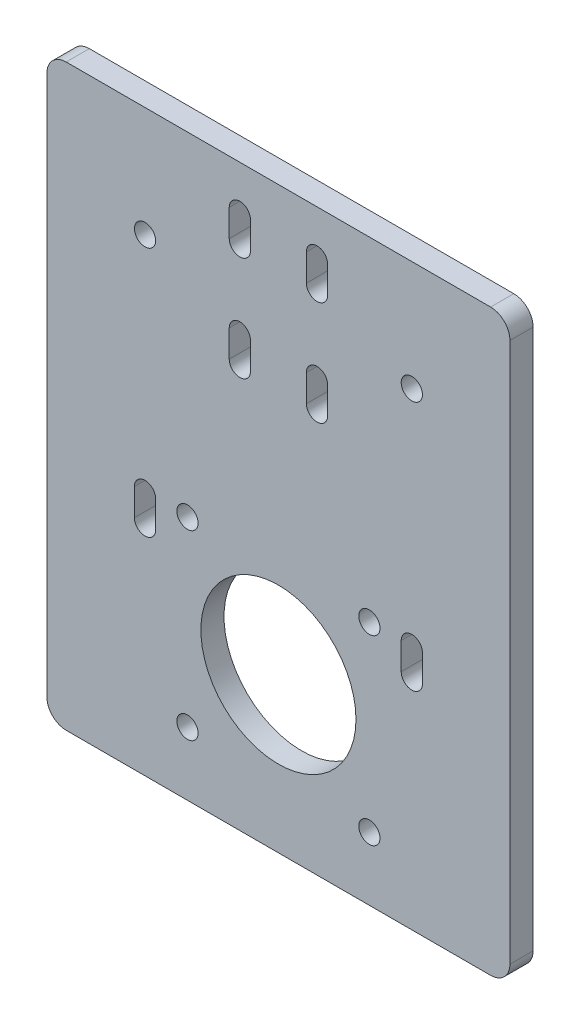
SolidWorks part; units mm, degrees
material "PET"
ref_plane "Front Plane" through (0, 0, 0) normal (0, 0, 1) x (1, 0, 0)
ref_plane "Top Plane" through (0, 0, 0) normal (0, 1, 0) x (1, 0, 0)
ref_plane "Right Plane" through (0, 0, 0) normal (1, 0, 0) x (0, 0, -1)
sketch "Sketch3" plane through (0, 0, 0) normal (0, 0, 1) x (1, 0, 0)
  line L1 (-55, -75) -> (55, -75)
  line L2 (-60, -70) -> (-60, 70)
  line L3 (-55, 75) -> (55, 75)
  line L4 (60, -70) -> (60, 70)
  line L5 (-60, -75) -> (60, 75) construction
  line L6 (-60, 75) -> (60, -75) construction
  arc A0 (-55, -75) -> (-60, -70) centre (-55, -70) cw
  arc A1 (55, -75) -> (60, -70) centre (55, -70) ccw
  arc A2 (55, 75) -> (60, 70) centre (55, 70) cw
  arc A3 (-60, 70) -> (-55, 75) centre (-55, 70) cw
  point P0 (0, 0)
  dimension "D3" = 5
  dimension "D1" = 120
  dimension "D2" = 150
extrude "Boss-Extrude1" add sketch "Sketch3" along normal blind 6
sketch "Sketch4" plane through (0, 0, 6) normal (0, 0, 1) x (1, 0, 0)
  line L0 (-55, -75) -> (55, -75) construction
  circle A0 centre (0, -35) radius 20.1
  dimension "D1" = 40.2
  dimension "D2" = 40
extrude "Cut-Extrude1" cut sketch "Sketch4" against normal blind 6
hole_wizard "M5 Clearance Hole1" positions "Sketch5" profile "Sketch6" hole size "M5" standard "ANSI Metric" end condition through all
sketch "Sketch5" plane through (0, 0, 6) normal (0, 0, 1) x (1, 0, 0)
  circle A0 centre (0, -35) radius 20.1 construction
  point P0 (-23.57, -11.43)
  point P2 (23.57, -11.43)
  point P4 (23.57, -58.57)
  point P6 (-23.57, -58.57)
  dimension "D2" = 23.57
  dimension "D3" = 23.57
  dimension "D5" = 23.57
  dimension "D1" = 47.14
  dimension "D4" = 23.57
sketch "Sketch6" plane through (-23.57, -11.43, 6) normal (1, 0, 0) x (0, -1, 0)
  line L0 (0, 0) -> (0, 6)
  line L1 (0, 6) -> (2.75, 6)
  line L2 (2.75, 6) -> (2.75, 0)
  line L5 (2.75, 0) -> (0, 0)
  line L11 (0, -6.35) -> (0, 107.95) construction
  dimension "Thru Hole Dia." = 5.5
  dimension "Thru Hole Depth" = 6
sketch "Sketch7" plane through (0, 0, 6) normal (0, 0, 1) x (1, 0, 0)
  line L0 (-34.57, -11.43) -> (-34.57, -18.43) construction
  line L1 (-31.82, -11.43) -> (-31.82, -18.43)
  line L2 (-37.32, -11.43) -> (-37.32, -18.43)
  line L3 (0, 37.3663) -> (0, -85.73) construction
  line L4 (34.57, -11.43) -> (34.57, -18.43) construction
  line L5 (31.82, -11.43) -> (31.82, -18.43)
  line L6 (37.32, -11.43) -> (37.32, -18.43)
  arc A0 (-31.82, -11.43) -> (-37.32, -11.43) centre (-34.57, -11.43) ccw
  arc A1 (-37.32, -18.43) -> (-31.82, -18.43) centre (-34.57, -18.43) ccw
  circle A2 centre (-23.57, -11.43) radius 2.75 construction
  arc A3 (31.82, -11.43) -> (37.32, -11.43) centre (34.57, -11.43) cw
  arc A4 (37.32, -18.43) -> (31.82, -18.43) centre (34.57, -18.43) cw
  point P2 (-34.57, -14.93)
  point P11 (34.57, -14.93)
  dimension "D1" = 2.75
  dimension "D2" = 7
  dimension "D3" = 11
extrude "Cut-Extrude2" cut sketch "Sketch7" against normal blind 6
hole_wizard "M5 Clearance Hole2" positions "Sketch8" profile "Sketch9" hole size "M5" standard "ANSI Metric" end condition through all
sketch "Sketch8" plane through (0, 0, 6) normal (0, 0, 1) x (1, 0, 0)
  point P0 (-34.57, 46.47)
  point P2 (34.57, 46.47)
  dimension "D1" = 61.4
sketch "Sketch9" plane through (-34.57, 46.47, 6) normal (1, 0, 0) x (0, -1, 0)
  line L0 (0, 0) -> (0, 6)
  line L1 (0, 6) -> (2.75, 6)
  line L2 (2.75, 6) -> (2.75, 0)
  line L5 (2.75, 0) -> (0, 0)
  line L11 (0, -6.35) -> (0, 107.95) construction
  dimension "Thru Hole Dia." = 5.5
  dimension "Thru Hole Depth" = 6
sketch "Sketch10" plane through (0, 0, 6) normal (0, 0, 1) x (1, 0, 0)
  line L0 (-10, 63.5) -> (-10, 56.5) construction
  line L1 (-7.25, 63.5) -> (-7.25, 56.5)
  line L2 (-12.75, 63.5) -> (-12.75, 56.5)
  line L3 (10, 63.5) -> (10, 56.5) construction
  line L4 (12.75, 63.5) -> (12.75, 56.5)
  line L5 (7.25, 63.5) -> (7.25, 56.5)
  line L6 (55, 75) -> (-55, 75) construction
  line L7 (34.57, 46.47) -> (-34.57, 46.47) construction
  line L8 (0, 37.3663) -> (0, -85.73) construction
  line L9 (-10, 29.44) -> (-10, 36.44) construction
  line L10 (-7.25, 29.44) -> (-7.25, 36.44)
  line L11 (-12.75, 29.44) -> (-12.75, 36.44)
  line L12 (10, 29.44) -> (10, 36.44) construction
  line L13 (12.75, 29.44) -> (12.75, 36.44)
  line L14 (7.25, 29.44) -> (7.25, 36.44)
  arc A0 (-7.25, 63.5) -> (-12.75, 63.5) centre (-10, 63.5) ccw
  arc A1 (-12.75, 56.5) -> (-7.25, 56.5) centre (-10, 56.5) ccw
  arc A2 (12.75, 63.5) -> (7.25, 63.5) centre (10, 63.5) ccw
  arc A3 (7.25, 56.5) -> (12.75, 56.5) centre (10, 56.5) ccw
  arc A4 (-7.25, 29.44) -> (-12.75, 29.44) centre (-10, 29.44) cw
  arc A5 (-12.75, 36.44) -> (-7.25, 36.44) centre (-10, 36.44) cw
  arc A6 (12.75, 29.44) -> (7.25, 29.44) centre (10, 29.44) cw
  arc A7 (7.25, 36.44) -> (12.75, 36.44) centre (10, 36.44) cw
  point P2 (-10, 60)
  point P7 (10, 60)
  point P28 (-10, 32.94)
  point P35 (10, 32.94)
  dimension "D1" = 2.75
  dimension "D2" = 7
  dimension "D3" = 15
  dimension "D4" = 20
  dimension "D5" = 10
extrude "Cut-Extrude3" cut sketch "Sketch10" against normal blind 6
sketch "Sketch11" plane through (0, 0, 0) normal (0, 0, -1) x (-1, 0, 0)
  line L0 (-41.0184, 46.47) -> (71.6367, 46.47) construction
